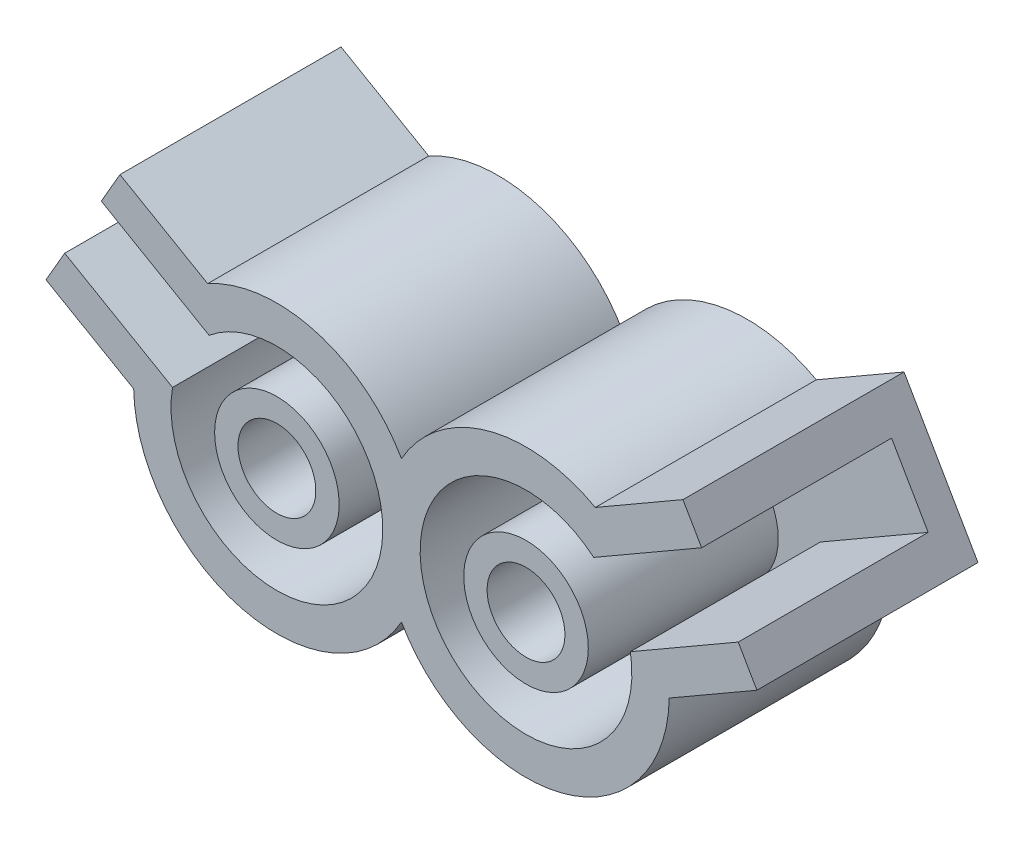
SolidWorks part; units mm, degrees
ref_plane "Front Plane" through (0, 0, 0) normal (0, 0, 1) x (1, 0, 0)
ref_plane "Top Plane" through (0, 0, 0) normal (0, 1, 0) x (1, 0, 0)
ref_plane "Right Plane" through (0, 0, 0) normal (1, 0, 0) x (0, 0, -1)
sketch "Sketch1" plane through (0, 0, 0) normal (0, 0, 1) x (1, 0, 0)
  line L0 (0, 0) -> (0, 7.8952) construction
  line L1 (4, 3.9476) -> (10.7779, 7.8608) construction
  line L2 (7.3506, 4.5253) -> (10.8147, 6.5253)
  line L3 (6.1756, 6.5604) -> (9.6397, 8.5604)
  line L4 (10.8147, 6.5253) -> (11.4147, 5.4861)
  line L5 (11.4147, 5.4861) -> (8.5992, 3.8605)
  line L6 (9.6397, 8.5604) -> (9.0397, 9.5997)
  line L7 (9.0397, 9.5997) -> (6.2242, 7.9741)
  line L8 (-9.0397, 9.5997) -> (-6.2242, 7.9741)
  line L9 (-9.6397, 8.5604) -> (-9.0397, 9.5997)
  line L10 (-11.4147, 5.4861) -> (-8.5992, 3.8605)
  line L11 (-10.8147, 6.5253) -> (-11.4147, 5.4861)
  line L12 (-6.1756, 6.5604) -> (-9.6397, 8.5604)
  line L13 (-7.3506, 4.5253) -> (-10.8147, 6.5253)
  line L14 (-0.6, 3.9476) -> (0.6, 3.9476) construction
  circle A0 centre (4, 3.9476) radius 2
  circle A1 centre (4, 3.9476) radius 3.4 construction
  arc A2 (6.1756, 6.5604) -> (7.3506, 4.5253) centre (4, 3.9476) ccw
  arc A3 (0, 1.676) -> (0, 6.2192) centre (4, 3.9476) ccw construction
  arc A4 (6.2242, 7.9741) -> (0, 6.2192) centre (4, 3.9476) ccw
  arc A5 (0, 1.676) -> (0, 6.2192) centre (-4, 3.9476) cw construction
  circle A6 centre (-4, 3.9476) radius 3.4 construction
  arc A7 (-6.2242, 7.9741) -> (0, 6.2192) centre (-4, 3.9476) cw
  arc A8 (-6.1756, 6.5604) -> (-7.3506, 4.5253) centre (-4, 3.9476) cw
  circle A9 centre (-4, 3.9476) radius 2
  arc A10 (0, 1.676) -> (8.5992, 3.8605) centre (4, 3.9476) ccw
  arc A11 (0, 1.676) -> (-8.5992, 3.8605) centre (-4, 3.9476) cw
  circle A12 centre (4, 3.9476) radius 1.25
  circle A13 centre (-4, 3.9476) radius 1.25
  point P15 (-0.6, 3.9476)
  point P18 (0.6137, 4.253)
  point P35 (0, 3.9476)
  dimension "D3" = 1.4
  dimension "D5" = 1.2
  dimension "D6" = 4
  dimension "D9" = 2.5
  dimension "D1" = 2.35
  dimension "D2" = 4
  dimension "D4" = 1.2
  dimension "D7" = 60
  dimension "D8" = 1.2
extrude "Boss-Extrude1" add sketch "Sketch1" along normal blind 6.1
sketch "Sketch2" plane through (0, 0, 0) normal (0, 0, -1) x (-1, 0, 0)
  line L0 (-9.6397, 8.5604) -> (-10.8147, 6.5253)
  line L1 (9.6397, 8.5604) -> (10.8147, 6.5253)
  line L12 (-7.3506, 4.5253) -> (-10.8147, 6.5253)
  line L13 (-10.8147, 6.5253) -> (-11.4147, 5.4861)
  line L14 (-11.4147, 5.4861) -> (-8.5992, 3.8605)
  line L15 (8.5992, 3.8605) -> (11.4147, 5.4861)
  line L16 (11.4147, 5.4861) -> (10.8147, 6.5253)
  line L17 (10.8147, 6.5253) -> (7.3506, 4.5253)
  line L18 (6.1756, 6.5604) -> (9.6397, 8.5604)
  line L19 (9.6397, 8.5604) -> (9.0397, 9.5997)
  line L20 (9.0397, 9.5997) -> (6.2242, 7.9741)
  line L21 (-6.2242, 7.9741) -> (-9.0397, 9.5997)
  line L22 (-9.0397, 9.5997) -> (-9.6397, 8.5604)
  line L23 (-9.6397, 8.5604) -> (-6.1756, 6.5604)
  line L25 (-10.8147, 6.5253) -> (-11.4147, 5.4861)
  line L26 (-11.4147, 5.4861) -> (-8.5992, 3.8605)
  line L27 (8.5992, 3.8605) -> (11.4147, 5.4861)
  line L28 (11.4147, 5.4861) -> (10.8147, 6.5253)
  line L31 (9.6397, 8.5604) -> (9.0397, 9.5997)
  line L32 (9.0397, 9.5997) -> (6.2242, 7.9741)
  line L33 (-6.2242, 7.9741) -> (-9.0397, 9.5997)
  line L34 (-9.0397, 9.5997) -> (-9.6397, 8.5604)
  arc A6 (-7.3506, 4.5253) -> (-6.1756, 6.5604) centre (-4, 3.9476) ccw
  arc A7 (-8.5992, 3.8605) -> (0, 1.676) centre (-4, 3.9476) ccw
  arc A8 (0, 1.676) -> (8.5992, 3.8605) centre (4, 3.9476) ccw
  arc A9 (6.1756, 6.5604) -> (7.3506, 4.5253) centre (4, 3.9476) ccw
  arc A10 (6.2242, 7.9741) -> (0, 6.2192) centre (4, 3.9476) ccw
  arc A11 (0, 6.2192) -> (-6.2242, 7.9741) centre (-4, 3.9476) ccw
  arc A13 (-8.5992, 3.8605) -> (0, 1.676) centre (-4, 3.9476) ccw
  arc A14 (0, 1.676) -> (8.5992, 3.8605) centre (4, 3.9476) ccw
  arc A16 (6.2242, 7.9741) -> (0, 6.2192) centre (4, 3.9476) ccw
  arc A17 (0, 6.2192) -> (-6.2242, 7.9741) centre (-4, 3.9476) ccw
  dimension "D1" = 0
extrude "Boss-Extrude2" add sketch "Sketch2" along normal blind 1
sketch "Sketch6" plane through (0, 0, 0) normal (0, 0, 1) x (1, 0, 0)
  circle A0 centre (4, 3.9476) radius 1.25 construction
  circle A1 centre (-4, 3.9476) radius 1.25 construction
  circle A2 centre (4, 3.9476) radius 1.25
  circle A3 centre (-4, 3.9476) radius 1.25
extrude "Cut-Extrude1" cut sketch "Sketch6" against normal up to next
